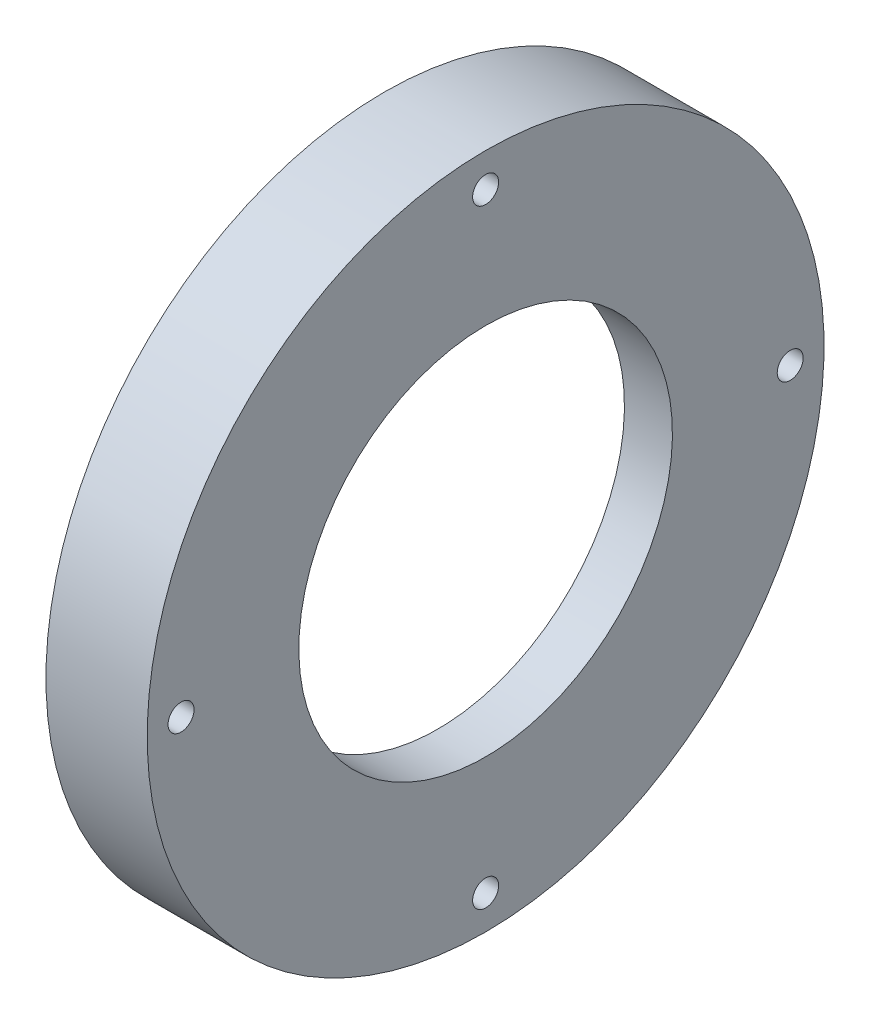
SolidWorks part; units mm, degrees
ref_plane "Front Plane" through (0, 0, 0) normal (0, 0, 1) x (1, 0, 0)
ref_plane "Top Plane" through (0, 0, 0) normal (0, 1, 0) x (1, 0, 0)
ref_plane "Right Plane" through (0, 0, 0) normal (1, 0, 0) x (0, 0, -1)
sketch "Sketch13" plane through (0, 0, 0) normal (0, 0, 1) x (1, 0, 0)
  line L0 (0, -31.75) -> (-9.5, -31.75)
  line L1 (-4.5, -26.75) -> (-4.5, -17.526)
  line L2 (-4.5, -17.526) -> (0, -17.526)
  line L3 (0, -17.526) -> (0, -31.75)
  line L7 (16.8808, 0) -> (-33.3573, 0) construction
  arc A0 (-9.5, -31.75) -> (-4.5, -26.75) centre (-9.5, -26.75) ccw
  dimension "D3" = 5
  dimension "D1" = 4.5
  dimension "D2" = 63.5
  dimension "D4" = 35.052
revolve "Revolve1" add sketch "Sketch13" angle 360 about L7
ref_plane "Edge plane" through (-9.5, 0, 0) normal (1, 0, 0) x (0, 0, -1)
hole_wizard "CBORE for #2 Binding Head Machine Screw1" positions "Sketch19" profile "Sketch18" counterbore size "#2" standard "Ansi Inch" end condition through all
sketch "Sketch19" plane through (-9.5, 0, 0) normal (1, 0, 0) x (0, 0, -1)
  line L0 (0, 28.575) -> (0, -28.575) construction
  line L3 (-28.575, 0) -> (28.575, 0) construction
  circle A0 centre (0, 0) radius 28.575
  point P0 (-28.575, 0)
  point P17 (0, 28.575)
  point P19 (28.575, 0)
  point P21 (0, -28.575)
  dimension "D1" = 57.15
sketch "Sketch18" plane through (-9.5, 0, 28.575) normal (0, 1, 0) x (0, 0, 1)
  line L0 (0, 0) -> (0, 9.5)
  line L1 (0, 9.5) -> (1.2192, 9.5)
  line L3 (1.2192, 9.5) -> (1.2192, 5.27)
  line L4 (1.2192, 5.27) -> (2.7788, 5.27)
  line L5 (2.7788, 5.27) -> (2.7788, 0)
  line L7 (2.7788, 0) -> (0, 0)
  line L11 (0, -6.35) -> (0, 107.95) construction
  dimension "Thru Hole Dia." = 2.4384
  dimension "Thru Hole Depth" = 9.5
  dimension "C'Bore Dia." = 5.5575
  dimension "C'Bore Depth" = 5.27
